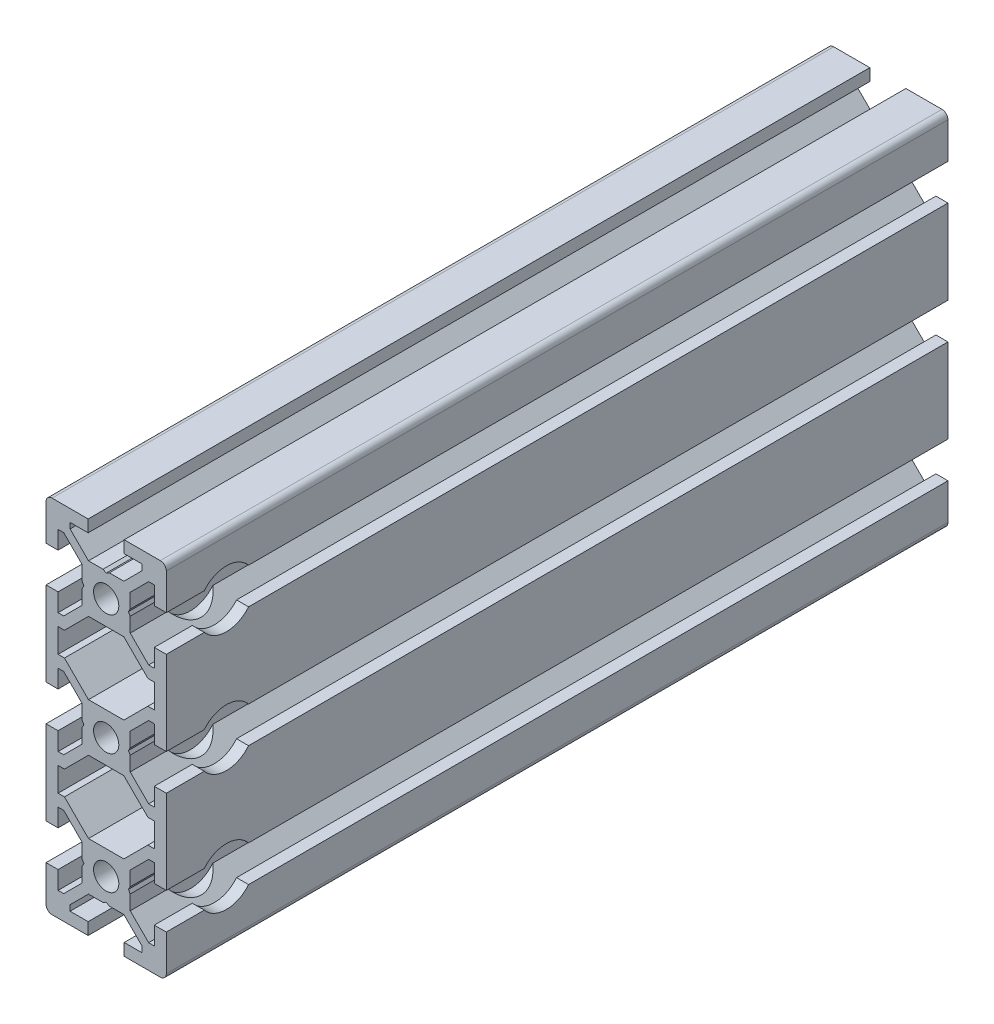
SolidWorks part; units mm, degrees
material "6061 Alloy"
ref_plane "Front Plane" through (0, 0, 0) normal (0, 0, 1) x (1, 0, 0)
ref_plane "Top Plane" through (0, 0, 0) normal (0, 1, 0) x (1, 0, 0)
ref_plane "Right Plane" through (0, 0, 0) normal (1, 0, 0) x (0, 0, -1)
ref_plane "Plane1" through (0, 0, 0) normal (0, 0, 1) x (1, 0, 0)
sketch "Sketch1" plane through (0, 0, 0) normal (0, 0, 1) x (1, 0, 0)
  line L0 (-10, -17) -> (-8, -17)
  line L1 (-8, -17) -> (-8, -14)
  line L2 (-8, -14) -> (-7.0607, -14)
  line L3 (-7.0607, -14) -> (-4, -17.0607)
  line L4 (-4, -17.0607) -> (-4, -19.4804)
  line L5 (-4, -19.4804) -> (-3.7, -20)
  line L6 (-3.7, -20) -> (-4, -20.5196)
  line L7 (-4, -20.5196) -> (-4, -22.9393)
  line L8 (-4, -22.9393) -> (-7.0607, -26)
  line L9 (-7.0607, -26) -> (-8, -26)
  line L10 (-8, -26) -> (-8, -23)
  line L11 (-8, -23) -> (-10, -23)
  line L12 (-10, -23) -> (-10, -29)
  line L13 (-9, -30) -> (-3, -30)
  line L14 (-3, -30) -> (-3, -28)
  line L15 (-3, -28) -> (-6, -28)
  line L16 (-6, -28) -> (-6, -27.0607)
  line L17 (-6, -27.0607) -> (-2.9393, -24)
  line L18 (-2.9393, -24) -> (-0.5196, -24)
  line L19 (-0.5196, -24) -> (0, -23.7)
  line L20 (0, -23.7) -> (0.5196, -24)
  line L21 (0.5196, -24) -> (2.9393, -24)
  line L22 (2.9393, -24) -> (6, -27.0607)
  line L23 (6, -27.0607) -> (6, -28)
  line L24 (6, -28) -> (3, -28)
  line L25 (3, -28) -> (3, -30)
  line L26 (3, -30) -> (9, -30)
  line L27 (10, -29) -> (10, -23)
  line L28 (10, -23) -> (8, -23)
  line L29 (8, -23) -> (8, -26)
  line L30 (8, -26) -> (7.0607, -26)
  line L31 (7.0607, -26) -> (4, -22.9393)
  line L32 (4, -22.9393) -> (4, -20.5196)
  line L33 (4, -20.5196) -> (3.7, -20)
  line L34 (3.7, -20) -> (4, -19.4804)
  line L35 (4, -19.4804) -> (4, -17.0607)
  line L36 (4, -17.0607) -> (7.0607, -14)
  line L37 (7.0607, -14) -> (8, -14)
  line L38 (8, -14) -> (8, -17)
  line L39 (8, -17) -> (10, -17)
  line L40 (10, -17) -> (10, -3)
  line L41 (10, -3) -> (8, -3)
  line L42 (8, -3) -> (8, -6)
  line L43 (8, -6) -> (7.0607, -6)
  line L44 (7.0607, -6) -> (4, -2.9393)
  line L45 (4, -2.9393) -> (4, -0.5196)
  line L46 (4, -0.5196) -> (3.7, 0)
  line L47 (3.7, 0) -> (4, 0.5196)
  line L48 (4, 0.5196) -> (4, 2.9393)
  line L49 (4, 2.9393) -> (7.0607, 6)
  line L50 (7.0607, 6) -> (8, 6)
  line L51 (8, 6) -> (8, 3)
  line L52 (8, 3) -> (10, 3)
  line L53 (10, 3) -> (10, 17)
  line L54 (10, 17) -> (8, 17)
  line L55 (8, 17) -> (8, 14)
  line L56 (8, 14) -> (7.0607, 14)
  line L57 (7.0607, 14) -> (4, 17.0607)
  line L58 (4, 17.0607) -> (4, 19.4804)
  line L59 (4, 19.4804) -> (3.7, 20)
  line L60 (3.7, 20) -> (4, 20.5196)
  line L61 (4, 20.5196) -> (4, 22.9393)
  line L62 (4, 22.9393) -> (7.0607, 26)
  line L63 (7.0607, 26) -> (8, 26)
  line L64 (8, 26) -> (8, 23)
  line L65 (8, 23) -> (10, 23)
  line L66 (10, 23) -> (10, 29)
  line L67 (9, 30) -> (3, 30)
  line L68 (3, 30) -> (3, 28)
  line L69 (3, 28) -> (6, 28)
  line L70 (6, 28) -> (6, 27.0607)
  line L71 (6, 27.0607) -> (2.9393, 24)
  line L72 (2.9393, 24) -> (0.5196, 24)
  line L73 (0.5196, 24) -> (0, 23.7)
  line L74 (0, 23.7) -> (-0.5196, 24)
  line L75 (-0.5196, 24) -> (-2.9393, 24)
  line L76 (-2.9393, 24) -> (-6, 27.0607)
  line L77 (-6, 27.0607) -> (-6, 28)
  line L78 (-6, 28) -> (-3, 28)
  line L79 (-3, 28) -> (-3, 30)
  line L80 (-3, 30) -> (-9, 30)
  line L81 (-10, 29) -> (-10, 23)
  line L82 (-10, 23) -> (-8, 23)
  line L83 (-8, 23) -> (-8, 26)
  line L84 (-8, 26) -> (-7.0607, 26)
  line L85 (-7.0607, 26) -> (-4, 22.9393)
  line L86 (-4, 22.9393) -> (-4, 20.5196)
  line L87 (-4, 20.5196) -> (-3.7, 20)
  line L88 (-3.7, 20) -> (-4, 19.4804)
  line L89 (-4, 19.4804) -> (-4, 17.0607)
  line L90 (-4, 17.0607) -> (-7.0607, 14)
  line L91 (-7.0607, 14) -> (-8, 14)
  line L92 (-8, 14) -> (-8, 17)
  line L93 (-8, 17) -> (-10, 17)
  line L94 (-10, 17) -> (-10, 3)
  line L95 (-10, 3) -> (-8, 3)
  line L96 (-8, 3) -> (-8, 6)
  line L97 (-8, 6) -> (-7.0607, 6)
  line L98 (-7.0607, 6) -> (-4, 2.9393)
  line L99 (-4, 2.9393) -> (-4, 0.5196)
  line L100 (-4, 0.5196) -> (-3.7, 0)
  line L101 (-3.7, 0) -> (-4, -0.5196)
  line L102 (-4, -0.5196) -> (-4, -2.9393)
  line L103 (-4, -2.9393) -> (-7.0607, -6)
  line L104 (-7.0607, -6) -> (-8, -6)
  line L105 (-8, -6) -> (-8, -3)
  line L106 (-8, -3) -> (-10, -3)
  line L107 (-10, -3) -> (-10, -17)
  line L108 (-8, 8) -> (-6.9393, 8)
  line L109 (-6.9393, 8) -> (-2.9393, 4)
  line L110 (-2.9393, 4) -> (2.9393, 4)
  line L111 (2.9393, 4) -> (6.9393, 8)
  line L112 (6.9393, 8) -> (8, 8)
  line L113 (8, 8) -> (8, 12)
  line L114 (8, 12) -> (6.9393, 12)
  line L115 (6.9393, 12) -> (2.9393, 16)
  line L116 (2.9393, 16) -> (-2.9393, 16)
  line L117 (-2.9393, 16) -> (-6.9393, 12)
  line L118 (-6.9393, 12) -> (-8, 12)
  line L119 (-8, 12) -> (-8, 8)
  line L120 (-8, -8) -> (-8, -12)
  line L121 (-8, -12) -> (-6.9393, -12)
  line L122 (-6.9393, -12) -> (-2.9393, -16)
  line L123 (-2.9393, -16) -> (2.9393, -16)
  line L124 (2.9393, -16) -> (6.9393, -12)
  line L125 (6.9393, -12) -> (8, -12)
  line L126 (8, -12) -> (8, -8)
  line L127 (8, -8) -> (6.9393, -8)
  line L128 (6.9393, -8) -> (2.9393, -4)
  line L129 (2.9393, -4) -> (-2.9393, -4)
  line L130 (-2.9393, -4) -> (-6.9393, -8)
  line L131 (-6.9393, -8) -> (-8, -8)
  arc A0 (-10, -29) -> (-9, -30) centre (-9, -29) ccw
  arc A1 (9, -30) -> (10, -29) centre (9, -29) ccw
  arc A2 (10, 29) -> (9, 30) centre (9, 29) ccw
  arc A3 (-9, 30) -> (-10, 29) centre (-9, 29) ccw
extrude "Boss-Extrude1" add sketch "Sketch1" against normal blind 130
ref_plane "Plane2" through (0, 0, 0) normal (1, 0, 0) x (0, 0, -1)
sketch "Sketch2" plane through (0, 0, 0) normal (1, 0, 0) x (0, 0, -1)
  line L0 (130, 20) -> (130, 17.9)
  line L1 (130, 17.9) -> (0, 17.9)
  line L2 (0, 17.9) -> (0, 20)
  line L3 (0, 20) -> (130, 20)
  line L4 (0, 20) -> (130, 20) construction
revolve "Cut-Revolve1" cut sketch "Sketch2" angle 360 about L4
ref_plane "Plane3" through (0, 0, 0) normal (1, 0, 0) x (0, 0, -1)
sketch "Sketch3" plane through (0, 0, 0) normal (1, 0, 0) x (0, 0, -1)
  line L0 (130, 0) -> (130, -2.1)
  line L1 (130, -2.1) -> (0, -2.1)
  line L2 (0, -2.1) -> (0, 0)
  line L3 (0, 0) -> (130, 0)
  line L4 (0, 0) -> (130, 0) construction
revolve "Cut-Revolve2" cut sketch "Sketch3" angle 360 about L4
ref_plane "Plane4" through (0, 0, 0) normal (1, 0, 0) x (0, 0, -1)
sketch "Sketch4" plane through (0, 0, 0) normal (1, 0, 0) x (0, 0, -1)
  line L0 (130, -20) -> (130, -22.1)
  line L1 (130, -22.1) -> (0, -22.1)
  line L2 (0, -22.1) -> (0, -20)
  line L3 (0, -20) -> (130, -20)
  line L4 (0, -20) -> (130, -20) construction
revolve "Cut-Revolve3" cut sketch "Sketch4" angle 360 about L4
ref_plane "Plane5" through (0, 20, 0) normal (0, 1, 0) x (1, 0, 0)
sketch "Sketch5" plane through (0, 20, 0) normal (0, 1, 0) x (1, 0, 0)
  line L0 (-10, 10) -> (-10, 12.75)
  line L1 (-10, 12.75) -> (4, 12.75)
  line L2 (4, 12.75) -> (4, 14.75)
  line L3 (4, 14.75) -> (10, 14.75)
  line L4 (10, 14.75) -> (10, 10)
  line L5 (10, 10) -> (-10, 10)
  line L6 (10, 10) -> (-10, 10) construction
revolve "Cut-Revolve4" cut sketch "Sketch5" angle 360 about L6
ref_plane "Plane6" through (0, 0, 0) normal (0, 1, 0) x (1, 0, 0)
sketch "Sketch6" plane through (0, 0, 0) normal (0, 1, 0) x (1, 0, 0)
  line L0 (-10, 10) -> (-10, 12.75)
  line L1 (-10, 12.75) -> (4, 12.75)
  line L2 (4, 12.75) -> (4, 14.75)
  line L3 (4, 14.75) -> (10, 14.75)
  line L4 (10, 14.75) -> (10, 10)
  line L5 (10, 10) -> (-10, 10)
  line L6 (10, 10) -> (-10, 10) construction
revolve "Cut-Revolve5" cut sketch "Sketch6" angle 360 about L6
ref_plane "Plane7" through (0, -20, 0) normal (0, 1, 0) x (1, 0, 0)
sketch "Sketch7" plane through (0, -20, 0) normal (0, 1, 0) x (1, 0, 0)
  line L0 (-10, 10) -> (-10, 12.75)
  line L1 (-10, 12.75) -> (4, 12.75)
  line L2 (4, 12.75) -> (4, 14.75)
  line L3 (4, 14.75) -> (10, 14.75)
  line L4 (10, 14.75) -> (10, 10)
  line L5 (10, 10) -> (-10, 10)
  line L6 (10, 10) -> (-10, 10) construction
revolve "Cut-Revolve6" cut sketch "Sketch7" angle 360 about L6
